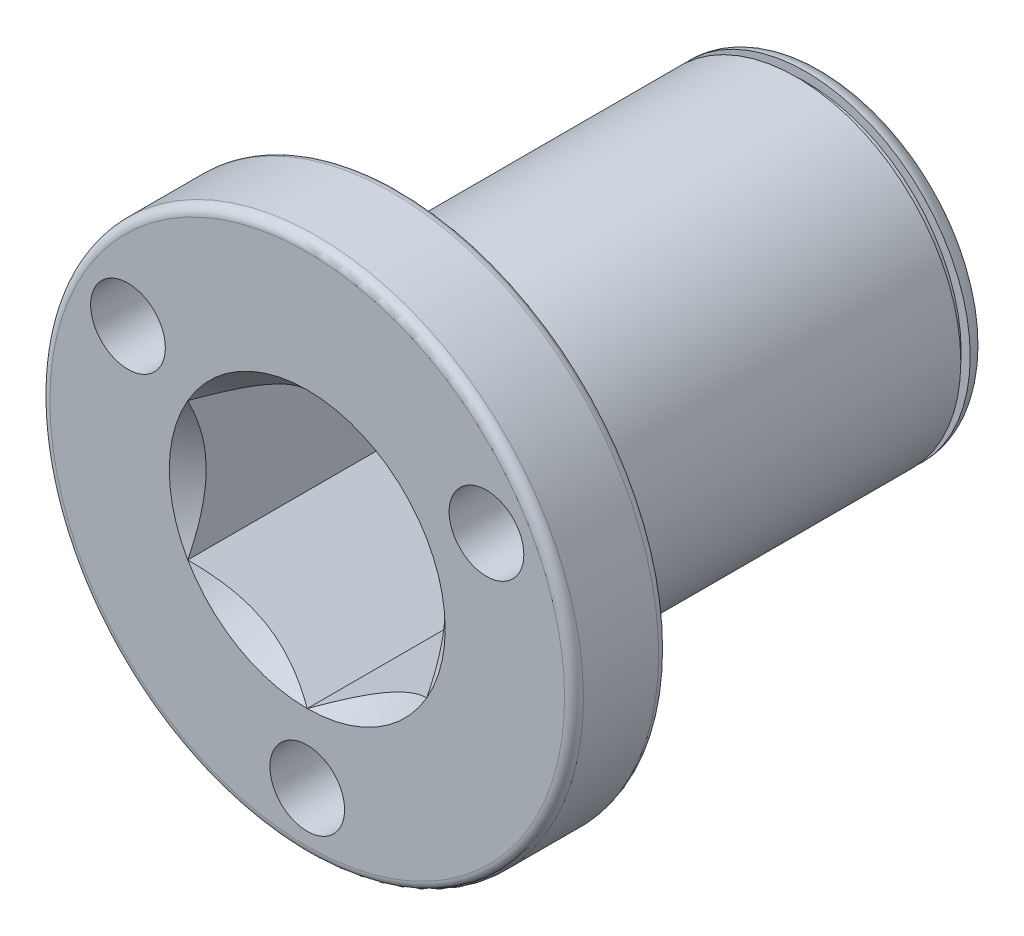
SolidWorks part; units mm, degrees
material "6061 Alloy"
ref_plane "Front Plane" through (0, 0, 0) normal (0, 0, 1) x (1, 0, 0)
ref_plane "Top Plane" through (0, 0, 0) normal (0, 1, 0) x (1, 0, 0)
ref_plane "Right Plane" through (0, 0, 0) normal (1, 0, 0) x (0, 0, -1)
sketch "Sketch1" plane through (0, 0, 0) normal (1, 0, 0) x (0, 0, -1)
  line L0 (0, 0) -> (55, 0)
  line L1 (55, 0) -> (55, 15.4625)
  line L2 (53, 17.4625) -> (11, 17.4625)
  line L3 (10, 18.4625) -> (10, 27.35)
  line L4 (9, 28.35) -> (1, 28.35)
  line L5 (0, 27.35) -> (0, 0)
  line L6 (53, 17.4625) -> (53, 16.5)
  line L7 (53, 16.5) -> (52, 16.5)
  line L8 (52, 16.5) -> (52, 17.4625)
  arc A0 (55, 15.4625) -> (53, 17.4625) centre (53, 15.4625) ccw
  arc A1 (10, 27.35) -> (9, 28.35) centre (9, 27.35) ccw
  arc A2 (1, 28.35) -> (0, 27.35) centre (1, 27.35) ccw
  arc A3 (11, 17.4625) -> (10, 18.4625) centre (11, 18.4625) cw
  point P11 (10, 28.35)
  point P14 (0, 28.35)
  dimension "D5" = 2
  dimension "D6" = 1
  dimension "D1" = 17.4625
  dimension "D2" = 28.35
  dimension "D3" = 10
  dimension "D4" = 55
  dimension "D7" = 1
  dimension "D8" = 16.5
revolve "Revolve1" add sketch "Sketch1" angle 360 about L0
sketch "Sketch2" plane through (0, 0, 0) normal (0, 0, 1) x (1, 0, 0)
  line L1 (0, 14.6647) -> (-12.7, 7.3323)
  line L2 (-12.7, 7.3323) -> (-12.7, -7.3323)
  line L3 (-12.7, -7.3323) -> (0, -14.6647)
  line L4 (0, -14.6647) -> (12.7, -7.3323)
  line L5 (12.7, -7.3323) -> (12.7, 7.3323)
  line L6 (12.7, 7.3323) -> (0, 14.6647)
  line L7 (-19.05, 10.9985) -> (0, -21.997)
  line L8 (0, -21.997) -> (19.05, 10.9985)
  line L9 (19.05, 10.9985) -> (-19.05, 10.9985)
  circle A0 centre (0, 0) radius 12.7 construction
  circle A1 centre (0, 0) radius 21.997 construction
  circle A2 centre (-19.05, 10.9985) radius 3.9688
  circle A3 centre (19.05, 10.9985) radius 3.9688
  circle A4 centre (0, -21.997) radius 3.9688
  dimension "D1" = 25.4
  dimension "D3" = 7.9375
  dimension "D4" = 7.9375
  dimension "D5" = 7.9375
  dimension "D2" = 38.1
extrude "Cut-Extrude1" cut sketch "Sketch2" against normal through all contours L6 L9 L1 L2 L7 L3 L4 L8 L5 | L9 L6 L1 | L7 L2 L3 | L8 L4 L5 | L9 A2 L7 | L7 A2 L9 | L8 A3 L9 | L9 A3 L8 | L7 A4 L8 | L8 A4 L7
sketch "Sketch3" plane through (0, 0, 0) normal (1, 0, 0) x (0, 0, -1)
  line L0 (0, 7.3323) -> (0, 14.6647) construction
  line L1 (0, 7.3323) -> (0, 14.6647)
  line L2 (0, 14.6647) -> (3.5, 11.1647)
  line L3 (3.5, 11.1647) -> (0, 11.1647)
  line L4 (55, 7.3323) -> (55, 14.6647) construction
  line L5 (55, 7.3323) -> (55, 14.6647)
  line L6 (55, 14.6647) -> (51.5, 11.1647)
  line L7 (51.5, 11.1647) -> (55, 11.1647)
  line L8 (55, 0) -> (0, 0) construction
  dimension "D1" = 3.5
  dimension "D2" = 45
  dimension "D3" = 3.5
  dimension "D4" = 45
revolve "Cut-Revolve2" cut sketch "Sketch3" angle 360 about L8
